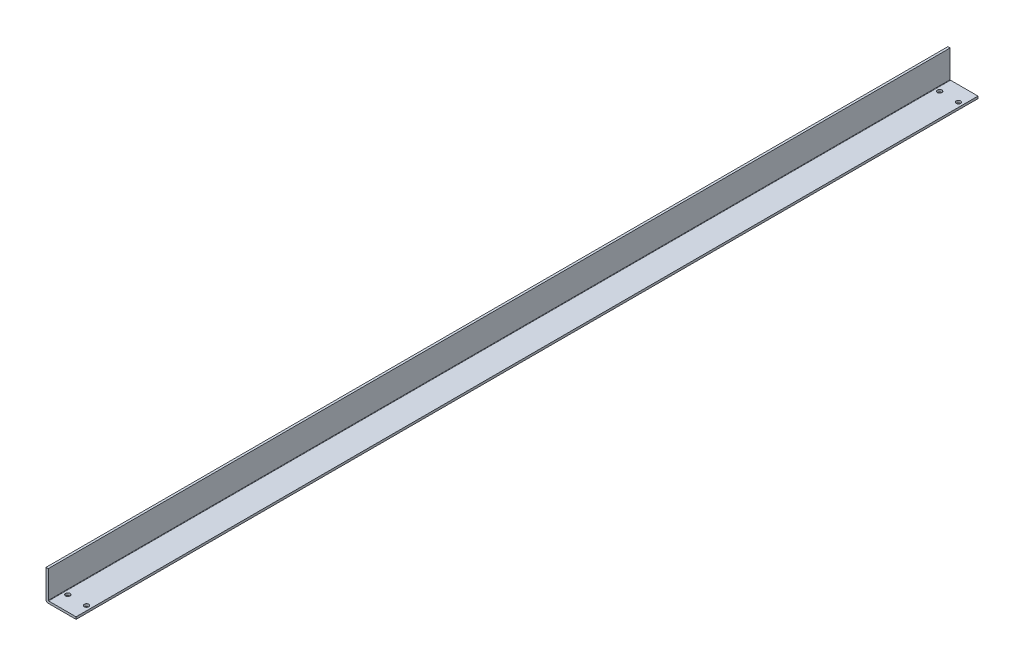
SolidWorks part; units mm, degrees
ref_plane "Front" through (0, 0, 0) normal (0, 0, 1) x (1, 0, 0)
ref_plane "Top" through (0, 0, 0) normal (0, 1, 0) x (1, 0, 0)
ref_plane "Right" through (0, 0, 0) normal (1, 0, 0) x (0, 0, -1)
sketch "Sketch1" plane through (0, 0, 0) normal (0, 0, 1) x (1, 0, 0)
  line L0 (0, 3) -> (0, 40)
  line L1 (0, 40) -> (3, 40)
  line L2 (3, 40) -> (3, 3.5)
  line L3 (3.5, 3) -> (40, 3)
  line L4 (40, 3) -> (40, 0)
  line L5 (40, 0) -> (3, 0)
  arc A0 (0, 3) -> (3, 0) centre (3, 3) ccw
  arc A1 (3, 3.5) -> (3.5, 3) centre (3.5, 3.5) ccw
  point P9 (0, 0)
  dimension "D5" = 3
  dimension "D6" = 0.5
  dimension "D1" = 40
  dimension "D2" = 40
  dimension "D3" = 3
  dimension "D4" = 3
extrude "Boss-Extrude1" add sketch "Sketch1" along normal blind 1200
sketch "Sketch2" plane through (0, 3, 0) normal (0, 1, 0) x (1, 0, 0)
  line L0 (40, -1200) -> (3.5, -1200) construction
  line L1 (0, -1200) -> (0, 0) construction
  line L2 (40, 0) -> (3.5, 0) construction
  line L3 (3.5, -1200) -> (3.5, 0) construction
  circle A0 centre (9, -1180) radius 3
  circle A1 centre (34, -1180) radius 3
  circle A2 centre (9, -20) radius 3
  circle A3 centre (34, -20) radius 3
  dimension "D1" = 6
  dimension "D4" = 6
  dimension "D9" = 6
  dimension "D10" = 6
  dimension "D2" = 20
  dimension "D3" = 9
  dimension "D5" = 25
  dimension "D6" = 9
  dimension "D7" = 25
  dimension "D8" = 20
extrude "Cut-Extrude1" cut sketch "Sketch2" against normal up to next
